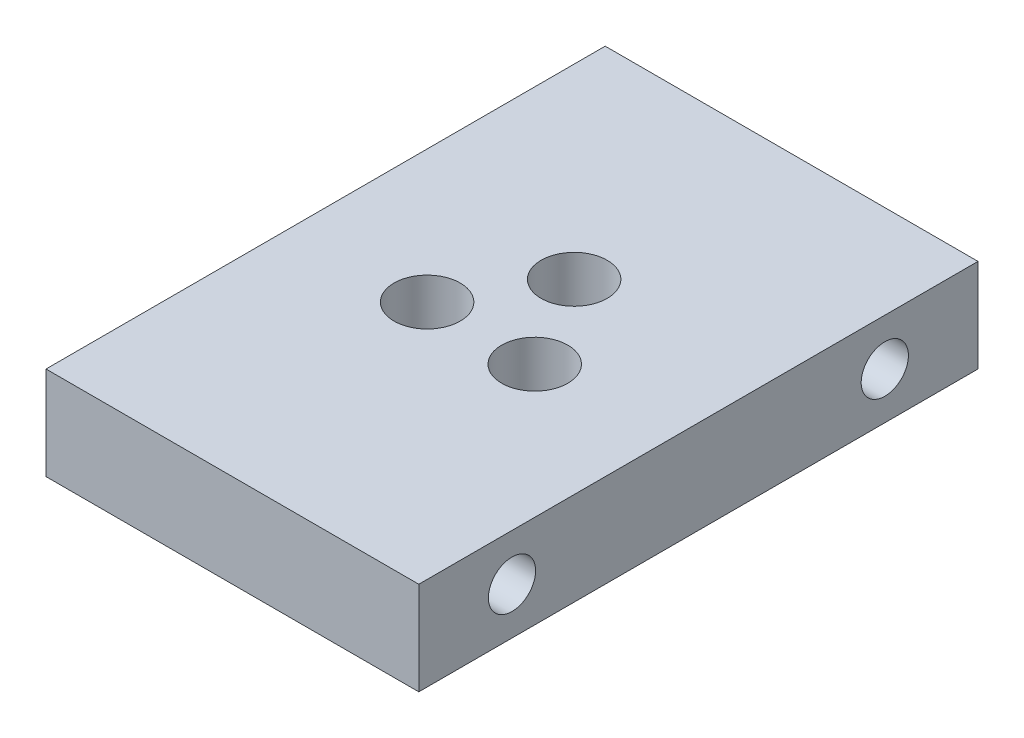
SolidWorks part; units mm, degrees
material "6061 Alloy"
ref_plane "Front Plane" through (0, 0, 0) normal (0, 0, 1) x (1, 0, 0)
ref_plane "Top Plane" through (0, 0, 0) normal (0, 1, 0) x (1, 0, 0)
ref_plane "Right Plane" through (0, 0, 0) normal (1, 0, 0) x (0, 0, -1)
sketch "Sketch1" plane through (0, 0, 0) normal (0, 1, 0) x (1, 0, 0)
  line L1 (-19.05, 28.575) -> (19.05, 28.575)
  line L2 (-19.05, 28.575) -> (-19.05, -28.575)
  line L3 (-19.05, -28.575) -> (19.05, -28.575)
  line L4 (19.05, 28.575) -> (19.05, -28.575)
  line L5 (-19.05, 28.575) -> (19.05, -28.575) construction
  line L6 (-19.05, -28.575) -> (19.05, 28.575) construction
  point P0 (0, 0)
  dimension "D1" = 57.15
  dimension "D2" = 38.1
extrude "Boss-Extrude1" add sketch "Sketch1" along normal blind 9.525
hole_wizard "CBORE for 1/4 Binding Head Machine Screw1" positions "Sketch3" profile "Sketch2" counterbore size "1/4" standard "ANSI Inch" end condition through all
sketch "Sketch3" plane through (0, 0, 0) normal (0, -1, 0) x (-1, 0, 0)
  point P4 (0, 6.35)
  point P21 (5.4993, -3.175)
  point P22 (-5.4993, -3.175)
  dimension "D1" = 6.35
  dimension "D2" = 3
sketch "Sketch2" plane through (0, 0, -6.35) normal (1, 0, 0) x (0, 0, -1)
  line L0 (0, 0) -> (0, 9.525)
  line L1 (0, 9.525) -> (3.3782, 9.525)
  line L3 (3.3782, 9.525) -> (3.3782, 4.191)
  line L4 (3.3782, 4.191) -> (7.1437, 4.191)
  line L5 (7.1437, 4.191) -> (7.1437, 0)
  line L7 (7.1437, 0) -> (0, 0)
  line L11 (0, -6.35) -> (0, 107.95) construction
  dimension "Thru Hole Dia." = 6.7564
  dimension "Thru Hole Depth" = 9.525
  dimension "C'Bore Dia." = 14.2875
  dimension "C'Bore Depth" = 4.191
hole_wizard "#10-32 Tapped Hole1" positions "3DSketch1" profile "Sketch4" tap size "#10-32" standard "ANSI Inch"
sketch3d "3DSketch1"
  line L4 (19.05, 4.7625, -19.05) -> (19.05, 4.7625, -28.575) construction
  line L5 (19.05, 9.525, -28.575) -> (19.05, 0, -28.575) construction
  line L7 (19.05, 4.7625, 19.05) -> (19.05, 4.7625, 28.575) construction
  line L8 (19.05, 9.525, 28.575) -> (19.05, 0, 28.575) construction
  point P0 (-19.05, 4.7625, -19.05)
  point P2 (-19.05, 4.7625, 19.05)
  point P4 (19.05, 4.7625, 19.05)
  point P6 (19.05, 4.7625, -19.05)
  dimension "D1" = 9.525
sketch "Sketch4" plane through (-19.05, 4.7625, -19.05) normal (0, 1, 0) x (0, 0, 1)
  line L0 (0, 0) -> (0, 13.9133)
  line L1 (0, 13.9133) -> (2.0193, 12.7)
  line L2 (2.0193, 12.7) -> (2.0193, 9.652)
  line L3 (2.0193, 9.652) -> (2.413, 9.652)
  line L4 (2.413, 9.652) -> (2.413, 0)
  line L5 (2.413, 0) -> (0, 0)
  line L10 (0, 13.9133) -> (-2.0193, 12.7) construction
  line L11 (0, -6.35) -> (0, 107.95) construction
  dimension "Tap Drill Dia." = 4.0386
  dimension "Tap Drill Depth" = 12.7
  dimension "Thread Major Dia." = 4.826
  dimension "Thread Depth" = 9.652
  dimension "Drill Angle" = 118
